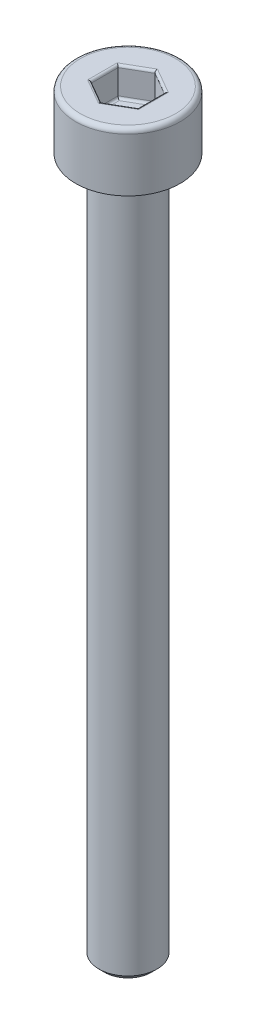
SolidWorks part; units mm, degrees
ref_plane "Front Plane" through (0, 0, 0) normal (0, 0, 1) x (1, 0, 0)
ref_plane "Top Plane" through (0, 0, 0) normal (0, 1, 0) x (1, 0, 0)
ref_plane "Right Plane" through (0, 0, 0) normal (1, 0, 0) x (0, 0, -1)
sketch "Sketch1" plane through (0, 0, 0) normal (0, 0, 1) x (1, 0, 0)
  line L0 (0, 0) -> (0, -47.0967) construction
  line L1 (0, -32.5) -> (-1.25, -32.5)
  line L2 (-1.25, -32.5) -> (-1.25, -2.5)
  line L3 (-1.25, -2.5) -> (-2.25, -2.5)
  line L4 (-2.25, -2.5) -> (-2.25, 0)
  line L5 (-2.25, 0) -> (0, 0)
  line L6 (0, 0) -> (0, -32.5)
  dimension "D1" = 30
  dimension "d" = 2.5
  dimension "k" = 2.5
  dimension "dk" = 4.5
revolve "Revolve1" add sketch "Sketch1" angle 360 about L0
chamfer "Chamfer1" distance 0.25 angle 45 2 edges at (0, -2.5, 1.25) (0, -32.5, 1.25)
fillet "Fillet1" radius 0.2 1 edges at (0, 0, 2.25)
sketch "Sketch2" plane through (0, 0, 0) normal (0, 1, 0) x (1, 0, 0)
  line L1 (0, 1.1547) -> (-1, 0.5774)
  line L2 (-1, 0.5774) -> (-1, -0.5774)
  line L3 (-1, -0.5774) -> (0, -1.1547)
  line L4 (0, -1.1547) -> (1, -0.5774)
  line L5 (1, -0.5774) -> (1, 0.5774)
  line L6 (1, 0.5774) -> (0, 1.1547)
  circle A0 centre (0, 0) radius 1 construction
  dimension "s" = 2
extrude "Cut-Extrude1" cut sketch "Sketch2" against normal blind 1.25
fillet "Fillet2" radius 0.1 12 edges at (-0.5, 0, -0.866) (-1, 0, 0) (-0.5, 0, 0.866) (0.5, 0, 0.866) (1, 0, 0) (0.5, 0, -0.866) (1, -1.25, 0) (0.5, -1.25, 0.866) (-0.5, -1.25, 0.866) (-1, -1.25, 0) (-0.5, -1.25, -0.866) (0.5, -1.25, -0.866)
